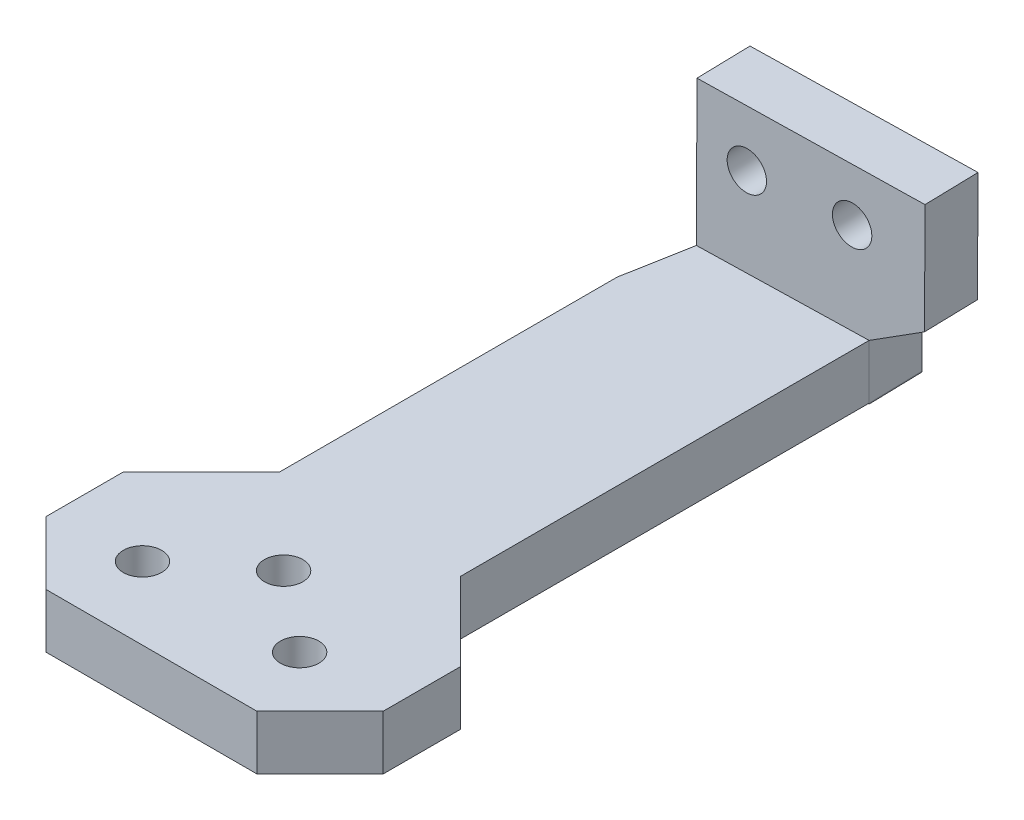
SolidWorks part; units mm, degrees
ref_plane "Front Plane" through (0, 0, 0) normal (0, 0, 1) x (1, 0, 0)
ref_plane "Top Plane" through (0, 0, 0) normal (0, 1, 0) x (1, 0, 0)
ref_plane "Right Plane" through (0, 0, 0) normal (1, 0, 0) x (0, 0, -1)
sketch "Sketch1" plane through (0, 0, 0) normal (0, 1, 0) x (1, 0, 0)
  line L0 (-18.7209, -104.8279) -> (-21.7565, -81.7705) construction
  line L1 (-19.6999, 14.5617) -> (19.6999, 14.5617)
  line L2 (-19.6999, 14.5617) -> (-19.6999, -97.3919)
  line L3 (-19.6999, -97.3919) -> (19.6999, -97.3919)
  line L4 (19.6999, 14.5617) -> (19.6999, -97.3919)
  point P6 (0, 14.5617)
extrude "Boss-Extrude1" add sketch "Sketch1" along normal blind 6.35
sketch "Sketch2" plane through (0, 0, 0) normal (0, -1, 0) x (1, 0, 0)
  circle A0 centre (-9.5292, 88.918) radius 2.2479
  circle A1 centre (-9.5292, 88.918) radius 3.05
  circle A3 centre (-9.5292, 88.918) radius 3.05 construction
  circle A5 centre (8.8374, 88.918) radius 3.05
  circle A7 centre (-6.8013, 8.7929) radius 2.8
  circle A8 centre (-6.8013, 8.7929) radius 2.8 construction
  circle A9 centre (6.8068, 8.4588) radius 2.8
  circle A10 centre (6.8068, 8.4588) radius 2.8 construction
  circle A11 centre (6.4644, -5.4854) radius 2.8
  circle A12 centre (6.4644, -5.4854) radius 2.8 construction
  circle A13 centre (-7.1437, -5.1513) radius 2.8
  circle A14 centre (-7.1437, -5.1513) radius 2.8 construction
  circle A15 centre (8.8374, 88.918) radius 3.05 construction
  circle A16 centre (-0.3459, 81.6071) radius 3.05
  circle A17 centre (-0.3459, 81.6071) radius 3.05 construction
  circle A18 centre (-0.3459, 81.6071) radius 2.2479
  circle A19 centre (8.8374, 88.918) radius 2.2479
  circle A20 centre (-6.8013, 8.7929) radius 2.2479
  circle A21 centre (6.8068, 8.4588) radius 2.2479
  circle A22 centre (6.4644, -5.4854) radius 2.2479
  circle A23 centre (-7.1437, -5.1513) radius 2.2479
  dimension "D8" = 4.4958
  dimension "D9" = 4.4958
  dimension "D1" = 0
  dimension "D2" = 0
  dimension "D3" = 0
  dimension "D4" = 0
  dimension "D5" = 0
  dimension "D6" = 0
  dimension "D7" = 0
extrude "Cut-Extrude1" cut sketch "Sketch2" against normal blind 6.35
sketch "Sketch3" plane through (0, 6.35, 0) normal (0, 1, 0) x (1, 0, 0)
  line L0 (-12.327, 14.5617) -> (-19.6999, 7.1889)
  line L1 (19.6999, 14.5617) -> (-19.6999, 14.5617) construction
  line L2 (-19.6999, 14.5617) -> (-19.6999, -97.3919) construction
  line L3 (-19.6999, 7.1889) -> (-19.6999, -12.745)
  line L4 (-19.6999, -12.745) -> (-10.5665, -21.8784)
  line L5 (-10.5665, -21.8784) -> (-10.5665, -71.8435)
  line L6 (-10.5665, -71.8435) -> (-19.6999, -80.9769)
  line L7 (-19.6999, -80.9769) -> (-19.6999, -90.0191)
  line L8 (-12.327, -97.3919) -> (12.327, -97.3919)
  line L9 (19.6999, -90.0191) -> (19.6999, -80.9769)
  line L10 (19.6999, -97.3919) -> (19.6999, 14.5617) construction
  line L11 (19.6999, -80.9769) -> (10.5665, -71.8435)
  line L12 (10.5665, -71.8435) -> (10.5665, -21.8784)
  line L13 (10.5665, -21.8784) -> (19.6999, -12.745)
  line L14 (19.6999, -12.745) -> (19.6999, 7.1889)
  line L15 (19.6999, 7.1889) -> (12.327, 14.5617)
  line L16 (12.327, 14.5617) -> (-12.327, 14.5617)
  line L17 (-12.327, -97.3919) -> (-19.6999, -90.0191)
  line L18 (-29.3118, 24.3499) -> (41.7609, 24.3499)
  line L19 (-29.3118, 24.3499) -> (-29.3118, -109.8733)
  line L20 (-29.3118, -109.8733) -> (41.7609, -109.8733)
  line L21 (41.7609, 24.3499) -> (41.7609, -109.8733)
  line L22 (12.327, -97.3919) -> (19.6999, -90.0191)
  line L23 (-19.6999, -97.3919) -> (19.6999, -97.3919) construction
  dimension "D1" = 45
  dimension "D2" = 45
extrude "Cut-Extrude2" cut sketch "Sketch3" against normal through all
sketch "Sketch4" plane through (0.4417, 0, 17.9912) normal (0.0245, 0, 0.9997) x (0.9997, 0, -0.0245)
  line L0 (16.3481, 23.2037) -> (-9.6666, 23.3181)
  line L1 (16.3481, 23.2037) -> (16.2455, -0.1144)
  line L2 (-9.6666, 23.3181) -> (-9.7692, 0)
  line L3 (16.2455, -0.1144) -> (-9.7692, 0)
  line L4 (9.4934, 23.2037) -> (18.5934, 23.2037) construction
  line L5 (-11.0114, 23.3181) -> (5.2837, 23.3181) construction
  line L7 (-14.7138, 0) -> (9.9328, 0) construction
extrude "Boss-Extrude2" add sketch "Sketch4" along normal blind 6.35
sketch "Sketch5" plane through (0, 6.35, 0) normal (0, 1, 0) x (1, 0, 0)
  line L0 (-34.0387, -18.8378) -> (44.2384, -16.9159)
  line L1 (-34.0387, -18.8378) -> (-34.9448, 18.0638)
  line L2 (44.2384, -16.9159) -> (43.3324, 19.9857)
  line L3 (-34.9448, 18.0638) -> (43.3324, 19.9857)
  line L4 (16.7849, -17.59) -> (-9.222, -18.2285) construction
extrude "Cut-Extrude3" cut sketch "Sketch5" against normal blind 17.78
sketch "Sketch7" plane through (0, 6.35, 0) normal (0, 1, 0) x (1, 0, 0)
  line L0 (-9.222, -18.2285) -> (-9.1407, -24.5784)
  line L1 (-9.1407, -24.5784) -> (-10.5665, -32.4087)
  line L2 (-10.5665, -21.8784) -> (-10.5665, -71.8435) construction
  line L3 (-10.5665, -32.4087) -> (-20.6658, -15.8135)
  line L4 (-20.6658, -15.8135) -> (-9.222, -18.2285)
extrude "Cut-Extrude4" cut sketch "Sketch7" against normal blind 17.78
sketch "Sketch8" plane through (0.5976, 0, 24.3393) normal (0.0245, 0, 0.9997) x (0.9997, 0, -0.0245)
  circle A0 centre (8.0329, 17.0846) radius 2.2479
  circle A1 centre (8.0329, 17.0846) radius 2.8
  circle A2 centre (8.0329, 17.0846) radius 2.8 construction
  circle A3 centre (-3.981, 16.7282) radius 2.8
  circle A4 centre (-3.981, 16.7282) radius 2.8 construction
  circle A5 centre (-3.981, 16.7282) radius 2.2479
  dimension "D3" = 4.4958
  dimension "D1" = 0
  dimension "D2" = 0
extrude "Cut-Extrude5" cut sketch "Sketch8" against normal blind 17.78
ref_plane "Plane1" through (10.5665, 6.35, 24.0946) normal (-0.9997, 0, 0.0245) x (0.0245, 0, 0.9997)
sketch "Sketch10" plane through (0.5976, 0, 24.3393) normal (0.0245, 0, 0.9997) x (0.9997, 0, -0.0245)
  line L0 (9.9719, 6.35) -> (16.2913, 10.296)
  line L1 (16.2455, -0.1144) -> (16.3481, 23.2037) construction
  line L2 (16.2913, 10.296) -> (16.2455, -0.1144)
  line L4 (9.9719, 0) -> (9.9719, 6.35)
  line L5 (9.9719, 0) -> (10.4421, -4.9121)
  line L6 (10.4421, -4.9121) -> (19.2573, -2.5862)
  line L7 (19.2573, -2.5862) -> (16.2455, -0.1144)
extrude "Cut-Extrude6" cut sketch "Sketch10" against normal blind 17.78
